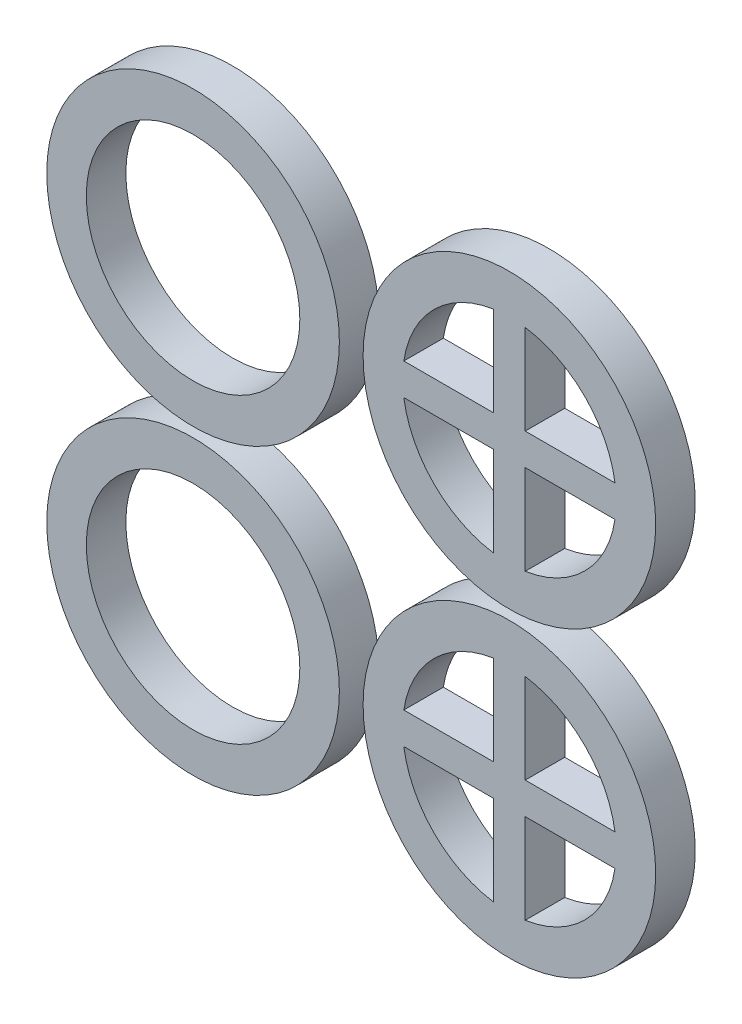
SolidWorks part; units mm, degrees
ref_plane "Front Plane" through (0, 0, 0) normal (0, 0, 1) x (1, 0, 0)
ref_plane "Top Plane" through (0, 0, 0) normal (0, 1, 0) x (1, 0, 0)
ref_plane "Right Plane" through (0, 0, 0) normal (1, 0, 0) x (0, 0, -1)
sketch "Sketch1" plane through (0, 0, 0) normal (0, 0, 1) x (1, 0, 0)
  line L0 (40, 13.5) -> (40, -13.5) construction
  line L1 (26.5, 0) -> (53.5, 0) construction
  line L2 (38, 13.351) -> (38, 2)
  line L3 (26.649, -2) -> (38, -2)
  line L4 (42, 13.351) -> (42, 2)
  line L5 (26.649, 2) -> (38, 2)
  line L6 (26.5, 2) -> (53.5, 2) construction
  line L7 (26.5, -2) -> (53.5, -2) construction
  line L8 (38, 13.5) -> (38, -13.5) construction
  line L9 (42, 13.5) -> (42, -13.5) construction
  line L10 (42, 2) -> (53.351, 2)
  line L11 (38, -2) -> (38, -13.351)
  line L12 (42, -2) -> (42, -13.351)
  line L13 (42, -2) -> (53.351, -2)
  line L14 (26.649, -36.2183) -> (38, -36.2183)
  line L15 (38, -40.2183) -> (38, -51.5693)
  line L16 (26.5, -38.2183) -> (53.5, -38.2183) construction
  line L17 (40, -24.7183) -> (40, -51.7183) construction
  line L18 (42, -40.2183) -> (53.351, -40.2183)
  line L19 (26.649, -40.2183) -> (38, -40.2183)
  line L20 (42, -36.2183) -> (53.351, -36.2183)
  line L21 (42, -40.2183) -> (42, -51.5693)
  line L22 (42, -24.8672) -> (42, -36.2183)
  line L23 (38, -24.8672) -> (38, -36.2183)
  circle A0 centre (0, 0) radius 13.5
  circle A1 centre (0, 0) radius 18.5
  arc A2 (38, 13.351) -> (26.649, 2) centre (40, 0) ccw
  circle A3 centre (40, 0) radius 18.5
  arc A4 (53.351, 2) -> (42, 13.351) centre (40, 0) ccw
  arc A5 (42, -13.351) -> (53.351, -2) centre (40, 0) ccw
  arc A6 (26.649, -2) -> (38, -13.351) centre (40, 0) ccw
  circle A7 centre (0, -38.2183) radius 18.5
  circle A8 centre (40, -38.2183) radius 18.5
  arc A9 (42, -51.5693) -> (53.351, -40.2183) centre (40, -38.2183) ccw
  circle A10 centre (0, -38.2183) radius 13.5
  arc A11 (38, -24.8672) -> (26.649, -36.2183) centre (40, -38.2183) ccw
  arc A12 (53.351, -36.2183) -> (42, -24.8672) centre (40, -38.2183) ccw
  arc A13 (26.649, -40.2183) -> (38, -51.5693) centre (40, -38.2183) ccw
  dimension "D1" = 27
  dimension "D2" = 5
  dimension "D4" = 27
  dimension "D5" = 5
  dimension "D8" = 27
  dimension "D11" = 27
  dimension "D3" = 40
  dimension "D10" = 40
  dimension "D12" = 32
  dimension "D6" = 2
  dimension "D7" = 2
extrude "Boss-Extrude1" add sketch "Sketch1" along normal blind 5
